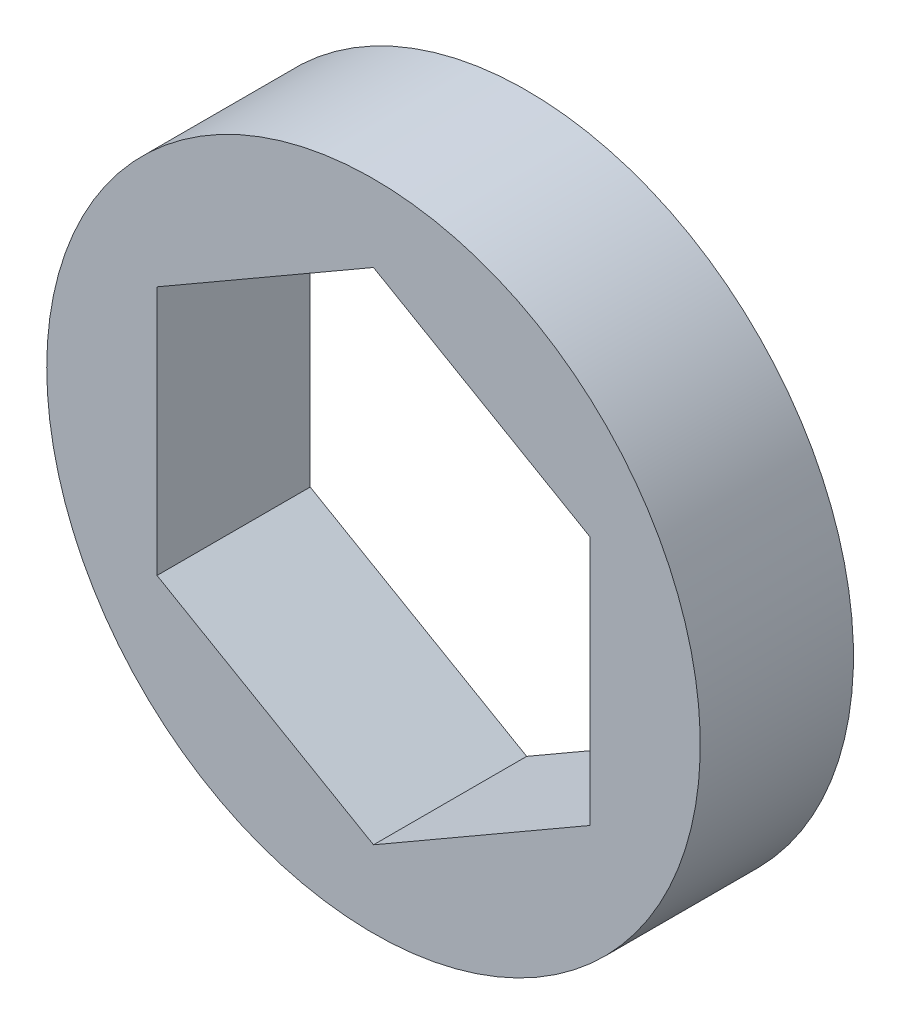
SolidWorks part; units mm, degrees
material "Nylon 101"
ref_plane "Front Plane" through (0, 0, 0) normal (0, 0, 1) x (1, 0, 0)
ref_plane "Top Plane" through (0, 0, 0) normal (0, 1, 0) x (1, 0, 0)
ref_plane "Right Plane" through (0, 0, 0) normal (1, 0, 0) x (0, 0, -1)
sketch "Sketch1" plane through (0, 0, 0) normal (0, 0, 1) x (1, 0, 0)
  line L1 (0, 7.7723) -> (-6.731, 3.8861)
  line L2 (-6.731, 3.8861) -> (-6.731, -3.8861)
  line L3 (-6.731, -3.8861) -> (0, -7.7723)
  line L4 (0, -7.7723) -> (6.731, -3.8861)
  line L5 (6.731, -3.8861) -> (6.731, 3.8861)
  line L6 (6.731, 3.8861) -> (0, 7.7723)
  circle A0 centre (0, 0) radius 10.16
  circle A1 centre (0, 0) radius 6.731 construction
  point P3 (0, 0)
  dimension "D1" = 20.32
  dimension "D2" = 13.462
extrude "Boss-Extrude1" add sketch "Sketch1" along normal mid plane 4.7625
